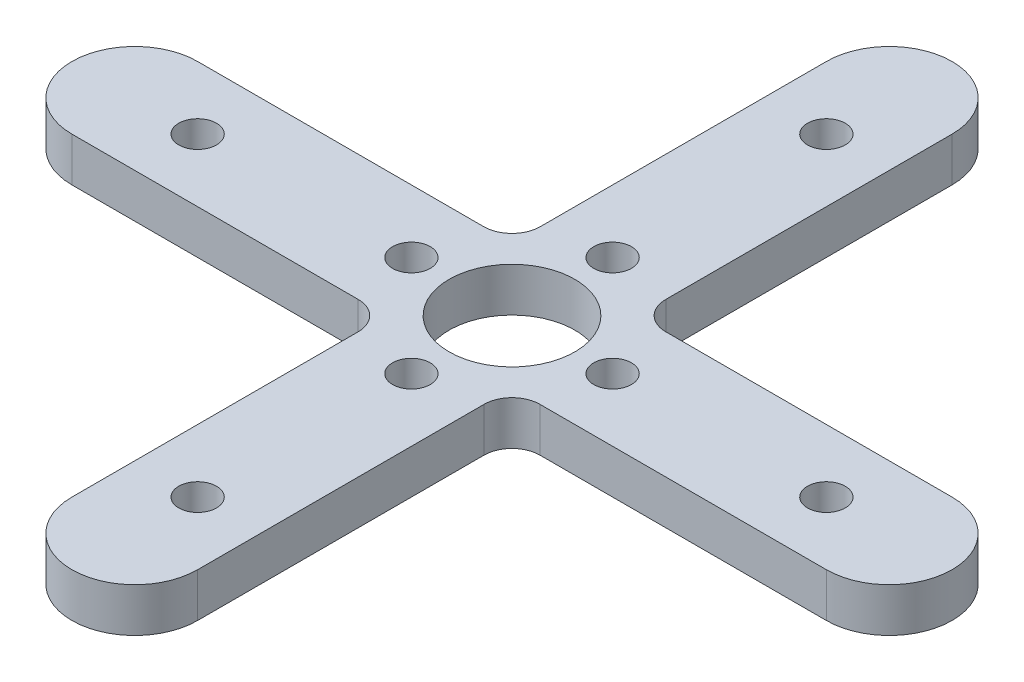
SolidWorks part; units mm, degrees
ref_plane "Alzado" through (0, 0, 0) normal (0, 0, 1) x (1, 0, 0)
ref_plane "Planta" through (0, 0, 0) normal (0, 1, 0) x (1, 0, 0)
ref_plane "Vista lateral" through (0, 0, 0) normal (1, 0, 0) x (0, 0, -1)
sketch "Croquis1" plane through (0, 0, 0) normal (0, 1, 0) x (1, 0, 0)
  line L0 (1.4757, 3.6958) -> (1.4757, 11.4846)
  line L6 (11.4757, 26.4535) -> (11.4757, 3.6555)
  line L7 (13.6977, 1.4535) -> (36.4757, 1.4535)
  line L15 (-23.5243, 1.4535) -> (-0.7665, 1.4535)
  line L16 (1.4757, -10.7887) -> (1.4757, -18.5775)
  line L17 (6.4757, -3.5465) -> (6.4757, 4.4535) construction
  line L18 (1.4757, -10.7887) -> (1.4757, -33.5465)
  line L19 (13.6977, -8.5465) -> (36.4757, -8.5465)
  line L20 (1.4757, 3.6958) -> (1.4757, 26.4535)
  line L21 (11.4757, -33.5465) -> (11.4757, -10.7484)
  line L22 (1.4757, -8.5775) -> (1.4757, -8.5465)
  line L23 (11.4757, -10.7484) -> (11.4757, -10.7887)
  line L24 (1.4757, -8.5465) -> (1.4757, -8.5775)
  line L25 (-23.5243, -8.5465) -> (-0.7665, -8.5465)
  line L26 (6.4757, -3.5465) -> (11.4757, -3.5465) construction
  line L29 (-17.0243, -3.5465) -> (-18.5243, -3.5465) construction
  line L30 (-0.0243, -3.5465) -> (-3.0243, -3.5465) construction
  line L31 (12.9757, -3.5465) -> (15.9757, -3.5465) construction
  circle A1 centre (6.4757, -3.5465) radius 5
  arc A2 (-0.7665, 1.4535) -> (1.4757, 3.6958) centre (-0.7665, 3.6958) ccw
  arc A4 (11.4757, -10.7484) -> (11.4757, -10.7887) centre (13.6977, -10.7685) ccw
  arc A5 (11.4757, 3.6958) -> (13.6977, 1.4535) centre (13.6977, 3.6756) ccw
  arc A6 (-23.5243, 1.4535) -> (-23.5243, -8.5465) centre (-23.5243, -3.5465) ccw
  arc A7 (36.4757, -8.5465) -> (36.4757, 1.4535) centre (36.4757, -3.5465) ccw
  arc A9 (11.4757, 26.4535) -> (1.4757, 26.4535) centre (6.4757, 26.4535) ccw
  arc A10 (11.4757, -10.7887) -> (13.6977, -8.5465) centre (13.6977, -10.7685) cw
  arc A11 (-0.7665, -8.5465) -> (1.4757, -10.7887) centre (-0.7665, -10.7887) cw
  arc A12 (1.4757, -33.5465) -> (11.4757, -33.5465) centre (6.4757, -33.5465) ccw
  circle A13 centre (-1.5243, -3.5465) radius 1.5
  circle A14 centre (14.4757, -3.5465) radius 1.5
  circle A15 centre (-18.5243, -3.5465) radius 1.5
  circle A16 centre (6.4757, 21.4535) radius 1.5
  circle A17 centre (31.4757, -3.5465) radius 1.5
  circle A18 centre (6.4757, -28.5465) radius 1.5
  circle A19 centre (6.4757, -11.5465) radius 1.5
  circle A20 centre (6.4757, 4.4535) radius 1.5
  point P0 (0, 0)
  dimension "D11" = 10
  dimension "D5" = 3
  dimension "D6" = 3
  dimension "D8" = 3
  dimension "D13" = 3
  dimension "D14" = 3
  dimension "D15" = 3
  dimension "D17" = 3
  dimension "D19" = 3
  dimension "D2" = 8
  dimension "D3" = 10
  dimension "D4" = 8
  dimension "D7" = 25
  dimension "D9" = 25
  dimension "D10" = 25
  dimension "D12" = 25
  dimension "D16" = 8
  dimension "D18" = 8
extrude "Saliente-Extruir2" add sketch "Croquis1" along normal blind 3.5
